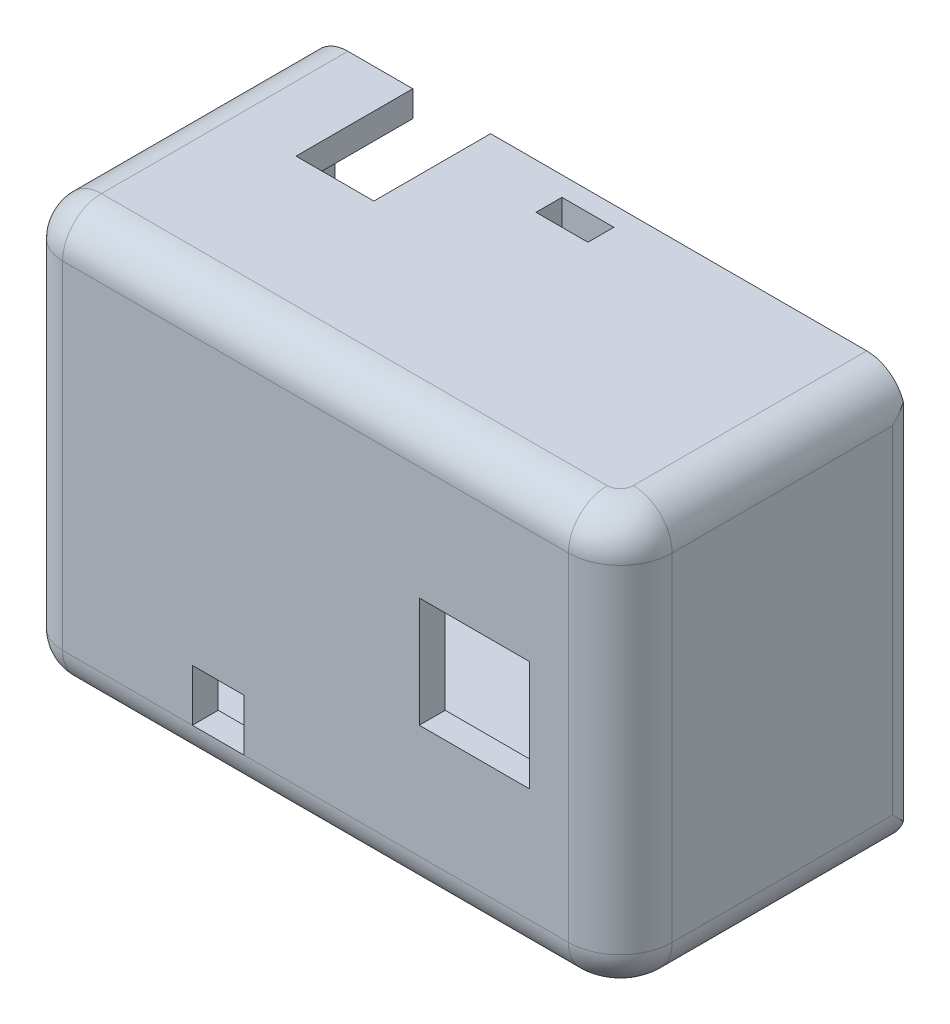
SolidWorks part; units mm, degrees
ref_plane "Front Plane" through (0, 0, 0) normal (0, 0, 1) x (1, 0, 0)
ref_plane "Top Plane" through (0, 0, 0) normal (0, 1, 0) x (1, 0, 0)
ref_plane "Right Plane" through (0, 0, 0) normal (1, 0, 0) x (0, 0, -1)
sketch "Sketch1" plane through (0, 0, 0) normal (0, 0, 1) x (1, 0, 0)
  line L0 (-2, 2) -> (44, 2)
  line L1 (0, 0) -> (42, 0)
  line L2 (0, 0) -> (0, -28)
  line L3 (0, -28) -> (42, -28)
  line L4 (42, 0) -> (42, -28)
  line L5 (44, 2) -> (44, -30)
  line L6 (-2, -30) -> (44, -30)
  line L7 (-2, 2) -> (-2, -30)
  dimension "D1" = 42
  dimension "D2" = 28
  dimension "D3" = 2
extrude "Boss-Extrude1" add sketch "Sketch1" along normal blind 20
sketch "Sketch2" plane through (0, 0, 0) normal (0, 0, -1) x (-1, 0, 0)
  line L1 (-44, 2) -> (2, 2)
  line L2 (-44, 2) -> (-44, -30)
  line L3 (-44, -30) -> (2, -30)
  line L4 (2, 2) -> (2, -30)
extrude "Boss-Extrude2" add sketch "Sketch2" along normal blind 2
sketch "Sketch3" plane through (0, -30, 0) normal (0, -1, 0) x (1, 0, 0)
  line L0 (44, -2) -> (-2, -2) construction
  line L1 (2, -2) -> (10, -2)
  line L2 (2, -2) -> (2, 4)
  line L3 (2, 4) -> (10, 4)
  line L4 (10, -2) -> (10, 4)
  line L5 (-2, 20) -> (-2, -2) construction
  line L6 (2, 0) -> (10, 0)
  dimension "D1" = 8
  dimension "D2" = 4
  dimension "D3" = 6
  dimension "D4" = 2
extrude "Cut-Extrude2" cut sketch "Sketch3" against normal through all contours L2 L6 L4 L3
sketch "Sketch4" plane through (-2, 0, 0) normal (-1, 0, 0) x (0, 0, 1)
  line L0 (-2, 2) -> (-2, -30)
  line L1 (-2, -14) -> (20, -14)
  line L2 (0, -9) -> (5, -9)
  line L3 (0, -9) -> (0, -19)
  line L4 (0, -19) -> (5, -19)
  line L5 (5, -9) -> (5, -19)
  line L6 (20, 2) -> (20, -30) construction
  dimension "D1" = 2
  dimension "D2" = 5
  dimension "D3" = 5
  dimension "D4" = 5
extrude "Cut-Extrude3" cut sketch "Sketch4" against normal blind 2 contours L5 L2 L3 L1 | L5 L1 L3 L4
sketch "Sketch5" plane through (0, 0, 20) normal (0, 0, 1) x (1, 0, 0)
  line L1 (-2, 2) -> (44, 2)
  line L2 (-2, 2) -> (-2, -30)
  line L3 (-2, -30) -> (44, -30)
  line L4 (44, 2) -> (44, -30)
extrude "Boss-Extrude3" add sketch "Sketch5" along normal blind 2
sketch "Sketch6" plane through (0, 0, 22) normal (0, 0, 1) x (1, 0, 0)
  line L0 (44, -14) -> (-2, -14)
  line L1 (28.5, -9.75) -> (37, -9.75)
  line L2 (28.5, -9.75) -> (28.5, -18.25)
  line L3 (28.5, -18.25) -> (37, -18.25)
  line L4 (37, -9.75) -> (37, -18.25)
  line L5 (44, -30) -> (44, 2) construction
  line L6 (-2, 2) -> (-2, -30) construction
  dimension "D1" = 7
  dimension "D2" = 4.25
  dimension "D3" = 4.25
  dimension "D4" = 8.5
extrude "Cut-Extrude4" cut sketch "Sketch6" against normal blind 2 contours L4 L1 L2 L0 | L4 L0 L2 L3
sketch "Sketch7" plane through (0, 0, 22) normal (0, 0, 1) x (1, 0, 0)
  line L8 (0, 0) -> (0, -28)
  line L9 (0, -28) -> (42, -28)
  line L10 (42, -28) -> (42, 0)
  line L11 (42, 0) -> (0, 0)
  line L12 (0, 0) -> (0, -28)
  line L13 (0, -28) -> (42, -28)
  line L14 (42, -28) -> (42, 0)
  line L15 (42, 0) -> (0, 0)
  line L23 (28.5, -9.75) -> (37, -9.75)
  line L24 (28.5, -9.75) -> (28.5, -18.25)
  line L25 (28.5, -18.25) -> (37, -18.25)
  line L26 (38.5, -19.75) -> (38.5, -8.25)
  line L27 (38.5, -8.25) -> (27, -8.25)
  line L28 (27, -8.25) -> (27, -19.75)
  line L29 (27, -19.75) -> (38.5, -19.75)
  line L30 (38.5, -19.75) -> (38.5, -8.25)
  line L31 (38.5, -8.25) -> (27, -8.25)
  line L32 (27, -8.25) -> (27, -19.75)
  line L33 (27, -19.75) -> (38.5, -19.75)
  line L34 (37, -9.75) -> (37, -18.25)
  line M13 (28.5, -9.75) -> (37, -9.75)
  line M14 (37, -9.75) -> (37, -18.25)
  line M15 (37, -18.25) -> (28.5, -18.25)
  line M16 (28.5, -18.25) -> (28.5, -9.75)
  dimension "D1" = 2
  dimension "D2" = 1.5
extrude "Boss-Extrude5" add sketch "Sketch7" along normal blind 2 contours L32 L33 L30 L31 M16 M13 M14 M15
sketch "Sketch9" plane through (0, 0, 24) normal (0, 0, 1) x (1, 0, 0)
  line L0 (27, -8.25) -> (38.5, -19.75)
  line L1 (38.5, -19.75) -> (38.5, -8.25)
  line L2 (38.5, -8.25) -> (27, -19.75)
  circle A0 centre (32.75, -14) radius 5
  circle A1 centre (32.75, -14) radius 5.75
  line M2 (28.5, -18.25) -> (28.5, -9.75)
  line M3 (28.5, -9.75) -> (37, -9.75)
  line M4 (37, -9.75) -> (37, -18.25)
  line M5 (37, -18.25) -> (28.5, -18.25)
extrude "Boss-Extrude8" add sketch "Sketch9" along normal blind 4 contours A1 M3 | A1 L0 A0 M3 | A1 M2 | L0 A1 A0 M2 | A1 L2 A0 M2 | L2 A1 A0 M5 | A1 M5 | A1 L0 A0 M5 | L0 A1 A0 M4 | A1 M4 | A1 L2 A0 M4 | L2 A1 A0 M3
sketch "Sketch11" plane through (0, 0, 24) normal (0, 0, 1) x (1, 0, 0)
  line L0 (38.5, -19.75) -> (27, -8.25)
  line L1 (27, -8.25) -> (38.5, -8.25)
  line L2 (38.5, -8.25) -> (27, -19.75)
  line L4 (27, -8.25) -> (38.5, -8.25)
  line L5 (27, -8.25) -> (27, -19.75)
  line L6 (27, -19.75) -> (38.5, -19.75)
  line L7 (38.5, -8.25) -> (38.5, -19.75)
  circle A0 centre (32.75, -14) radius 6.5
  arc M1 (36.623, -18.25) -> (32.75, -19.75) centre (32.75, -14) cw
  line M2 (32.75, -19.75) -> (38.5, -19.75)
  line M3 (38.5, -19.75) -> (38.5, -14)
  arc M4 (38.5, -14) -> (37, -17.873) centre (32.75, -14) cw
  line M5 (37, -17.873) -> (37, -18.25)
  line M6 (37, -18.25) -> (36.623, -18.25)
extrude "Boss-Extrude9" add sketch "Sketch11" along normal blind 0.5 contours A0 L0 L5 | A0 L1 L0 | A0 L2 L4 | A0 L7 L2 | L0 M3 M4 M5 | L0 M2 M6 M1 | A0 L2 L6 | A0 L5 L2 | A0 L0 M6 | A0 L0 M5
fillet "Fillet2" radius 4 1 edges at (44, -14, 22)
fillet "Fillet3" radius 3 7 edges at (19, -30, 22) (42.8284, -30, 20.8284) (19, 2, 22) (42.8284, 2, 20.8284) (44, -30, 8) (44, -14, -2) (44, 2, 8)
fillet "Fillet4" radius 2 4 edges at (38.5, -19.75, 23.25) (27, -19.75, 23.25) (27, -8.25, 23.25) (38.5, -8.25, 23.25)
sketch "Sketch13" plane through (0, 0, -2) normal (0, 0, -1) x (-1, 0, 0)
  line L1 (-41, 2) -> (2, 2)
  line L2 (-41, 2) -> (-41, -30)
  line L3 (-41, -30) -> (2, -30)
  line L4 (2, 2) -> (2, -30)
extrude "Cut-Extrude5" cut sketch "Sketch13" against normal blind 2
sketch "Sketch14" plane through (41, 0, 0) normal (-1, 0, 0) x (0, 0, 1)
  line L1 (-2, 2) -> (0, 2)
  line L2 (-2, 2) -> (-2, -30)
  line L3 (-2, -30) -> (0, -30)
  line L4 (0, 2) -> (0, -30)
extrude "Cut-Extrude6" cut sketch "Sketch14" against normal blind 2
sketch "Sketch15" plane through (0, 0, 22) normal (0, 0, 1) x (1, 0, 0)
  line L0 (-2, -27) -> (40, -27) construction
  line L1 (11, -23) -> (15, -23)
  line L2 (11, -23) -> (11, -27)
  line L3 (11, -27) -> (15, -27)
  line L4 (15, -23) -> (15, -27)
  line L5 (-2, -1) -> (-2, -27) construction
  dimension "D1" = 4
  dimension "D2" = 4
  dimension "D3" = 0
  dimension "D4" = 13
extrude "Cut-Extrude9" cut sketch "Sketch15" against normal blind 2
sketch "Sketch16" plane through (43, 0, 0) normal (-1, 0, 0) x (0, 0, 1)
  line L1 (-1.2361, 1.2361) -> (0, 1.2361)
  line L2 (-1.2361, 1.2361) -> (-1.2361, -29.2361)
  line L3 (-1.2361, -29.2361) -> (0, -29.2361)
  line L4 (0, 1.2361) -> (0, -29.2361)
extrude "Cut-Extrude10" cut sketch "Sketch16" against normal blind 2
fillet "Fillet9" radius 3 5 edges at (-2, -29.1213, 21.1213) (-2, -14, 22) (-2, 1.1213, 21.1213) (-2, -30, 9.5) (-2, 2, 9.5)
sketch "Sketch19" plane through (0, -30, 0) normal (0, -1, 0) x (1, 0, 0)
  line L0 (1, 22) -> (11, 22) construction
  line L1 (19, 3.5) -> (23, 3.5)
  line L2 (19, 3.5) -> (19, 1.5)
  line L3 (19, 1.5) -> (23, 1.5)
  line L4 (23, 3.5) -> (23, 1.5)
  line L5 (41, 0) -> (10, 0) construction
  line L7 (44, 18) -> (44, 1) construction
  line L9 (-2, 0) -> (-2, 19) construction
  point P6 (19, 2.5)
  dimension "D1" = 18.5
  dimension "D2" = 2
  dimension "D3" = 21
  dimension "D4" = 21
  dimension "D5" = 1.5
extrude "Cut-Extrude11" cut sketch "Sketch19" along normal through all both and the other way through all
sketch "Sketch21" plane through (0, 2, 0) normal (0, 1, 0) x (1, 0, 0)
  line L1 (10, 0) -> (12, 0)
  line L2 (10, 0) -> (10, -4)
  line L3 (10, -4) -> (12, -4)
  line L4 (12, 0) -> (12, -4)
  dimension "D1" = 2
extrude "Cut-Extrude12" cut sketch "Sketch21" against normal mid plane 110
sketch "Sketch22" plane through (0, 2, 0) normal (0, 1, 0) x (1, 0, 0)
  line L0 (2, -4) -> (12, -4) construction
  line L1 (2, 0) -> (6, 0)
  line L2 (2, 0) -> (2, -4)
  line L3 (2, -4) -> (6, -4)
  line L4 (6, 0) -> (6, -4)
  dimension "D1" = 4
extrude "Boss-Extrude10" add sketch "Sketch22" against normal blind 2
sketch "Sketch23" plane through (0, -30, 0) normal (0, -1, 0) x (1, 0, 0)
  line L1 (2, 4) -> (6, 4)
  line L2 (2, 4) -> (2, 0)
  line L3 (2, 0) -> (6, 0)
  line L4 (6, 4) -> (6, 0)
extrude "Boss-Extrude11" add sketch "Sketch23" against normal blind 2
sketch "Sketch24" plane through (0, -30, 0) normal (0, -1, 0) x (1, 0, 0)
  line L1 (12, 4) -> (12, 0) construction
  line L2 (6, 4) -> (12, 4)
  line L3 (6, 4) -> (6, 9)
  line L4 (6, 9) -> (12, 9)
  line L5 (12, 4) -> (12, 9)
  dimension "D1" = 0
  dimension "D2" = 5
extrude "Cut-Extrude13" cut sketch "Sketch24" against normal mid plane 93
sketch "Sketch25" plane through (-2, 0, 0) normal (-1, 0, 0) x (0, 0, 1)
  line L0 (0, -19) -> (5, -19) construction
  line L1 (5, -9) -> (10, -9)
  line L2 (5, -9) -> (5, -19)
  line L3 (5, -19) -> (10, -19)
  line L4 (10, -9) -> (10, -19)
  dimension "D1" = 0
  dimension "D2" = 5
extrude "Cut-Extrude14" cut sketch "Sketch25" against normal blind 13
sketch "Sketch26" plane through (0, 0, 28) normal (0, 0, 1) x (1, 0, 0)
  circle A0 centre (32.75, -14) radius 5
  circle A1 centre (32.75, -14) radius 6.5
extrude "Cut-Extrude15" cut sketch "Sketch26" against normal up to surface (3.5 mm away)
sketch "Sketch27" plane through (0, 0, 24.5) normal (0, 0, 1) x (1, 0, 0)
  line L0 (36.5, -8.25) -> (29, -8.25) construction
  line L1 (27, -8.25) -> (38.5, -8.25)
  line L2 (27, -8.25) -> (27, -19.75)
  line L3 (27, -19.75) -> (38.5, -19.75)
  line L4 (38.5, -8.25) -> (38.5, -19.75)
  line L5 (29, -19.75) -> (36.5, -19.75) construction
  line L6 (27, -10.25) -> (27, -17.75) construction
  line L7 (38.5, -17.75) -> (38.5, -10.25) construction
  dimension "D1" = 0
  dimension "D2" = 0
extrude "Cut-Extrude16" cut sketch "Sketch27" against normal up to surface (2.5 mm away) up to face at (16.75, -19.5, 22)
